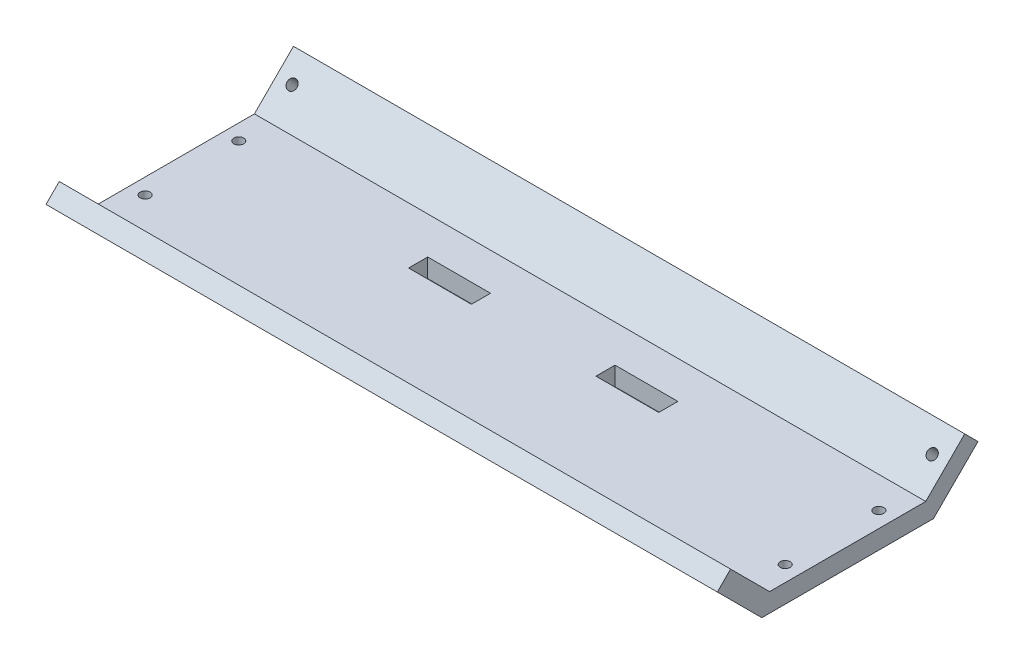
SolidWorks part; units mm, degrees
ref_plane "Front Plane" through (0, 0, 0) normal (0, 0, 1) x (1, 0, 0)
ref_plane "Top Plane" through (0, 0, 0) normal (0, 1, 0) x (1, 0, 0)
ref_plane "Right Plane" through (0, 0, 0) normal (1, 0, 0) x (0, 0, -1)
sketch "Sketch2" plane through (0, 0, 0) normal (1, 0, 0) x (0, 0, -1)
  line L0 (-25, 0) -> (25, 0)
  line L1 (25, 0) -> (37.5, 12.5)
  line L2 (-25, 0) -> (-37.5, 12.5)
  line L8 (27.4853, -6) -> (41.7426, 8.2574)
  line L9 (-27.4853, -6) -> (27.4853, -6)
  line L10 (-27.4853, -6) -> (-41.7426, 8.2574)
  line L11 (-37.5, 12.5) -> (-41.7426, 8.2574)
  line L12 (37.5, 12.5) -> (41.7426, 8.2574)
  line L13 (-37.5, 12.5) -> (-50, 25) construction
  line L14 (37.5, 12.5) -> (50, 25) construction
  point P4 (0, 0)
  dimension "D2" = 135
  dimension "D3" = 135
  dimension "D1" = 100
  dimension "D4" = 25
  dimension "D5" = 6
extrude "Main" add sketch "Sketch2" along normal mid plane 215
hole_wizard "Ø4.0mm Dowel Hole2" positions "3DSketch2" profile "Sketch4" hole size "Ø4.0" standard "ANSI Metric" end condition through all
sketch3d "3DSketch2"
  line L2 (107.5, 0, -25) -> (-107.5, 0, -25) construction
  line L3 (-102.5, 0, -25) -> (-102.5, 0, -15) construction
  line L4 (-102.5, 0, -15) -> (-102.5, 0, 15) construction
  line L5 (-102.5, 0, 15) -> (-102.5, 0, 25) construction
  line L6 (107.5, 0, 25) -> (-107.5, 0, 25) construction
  line L11 (102.5, 0, -25) -> (102.5, 0, -15) construction
  line L12 (102.5, 0, -15) -> (102.5, 0, 15) construction
  line L13 (102.5, 0, 15) -> (102.5, 0, 25) construction
  line L27 (102.5, 0, -25) -> (102.5, 7.0711, -32.0711) construction
  line L29 (102.5, 0, 25) -> (102.5, 7.0711, 32.0711) construction
  line L31 (-102.5, 7.0711, 32.0711) -> (-102.5, 0, 25) construction
  line L35 (-102.5, 7.0711, -32.0711) -> (-107.5, 7.0711, -32.0711) construction
  line L36 (-107.5, 12.5, -37.5) -> (-107.5, 0, -25) construction
  line L38 (-102.5, 7.0711, 32.0711) -> (-107.5, 7.0711, 32.0711) construction
  line L39 (-107.5, 0, 25) -> (-107.5, 12.5, 37.5) construction
  line L41 (102.5, 7.0711, -32.0711) -> (107.5, 7.0711, -32.0711) construction
  line L42 (107.5, 12.5, -37.5) -> (107.5, 0, -25) construction
  line L44 (102.5, 7.0711, 32.0711) -> (107.5, 7.0711, 32.0711) construction
  line L45 (107.5, 0, 25) -> (107.5, 12.5, 37.5) construction
  line L47 (102.5, 0, 25) -> (107.5, 0, 25) construction
  line L49 (-102.5, 0, 25) -> (-107.5, 0, 25) construction
  line L51 (-102.5, 7.0711, -32.0711) -> (-102.5, 0, -25) construction
  point P0 (-102.5, 7.0711, -32.0711)
  point P2 (-102.5, 0, -15)
  point P4 (-102.5, 0, 15)
  point P6 (-102.5, 7.0711, 32.0711)
  point P8 (102.5, 7.0711, 32.0711)
  point P10 (102.5, 0, 15)
  point P12 (102.5, 0, -15)
  point P14 (102.5, 7.0711, -32.0711)
  dimension "D1" = 5
  dimension "D2" = 10
  dimension "D3" = 10
sketch "Sketch4" plane through (-102.5, 7.0711, -32.0711) normal (1, 0, 0) x (0, -0.7071, 0.7071)
  line L0 (0, 0) -> (0, 16.0815)
  line L1 (0, 16.0815) -> (1.6, 16.0815)
  line L2 (1.6, 16.0815) -> (1.6, 0)
  line L5 (1.6, 0) -> (0, 0)
  line L11 (0, -6.35) -> (0, 107.95) construction
  dimension "Thru Hole Dia." = 3.2
  dimension "Thru Hole Depth" = 16.0815
sketch "Sketch5" plane through (0, 0, 0) normal (0, 1, 0) x (1, 0, 0)
  line L1 (-33.5, 21) -> (33.5, 21) construction
  line L2 (-33.5, 21) -> (-33.5, -21) construction
  line L3 (-33.5, -21) -> (33.5, -21) construction
  line L4 (33.5, 21) -> (33.5, -21) construction
  line L5 (-33.5, 21) -> (33.5, -21) construction
  line L6 (-33.5, -21) -> (33.5, 21) construction
  circle A0 centre (-33.5, 21) radius 3.5
  circle A1 centre (33.5, 21) radius 3.5
  circle A2 centre (-33.5, -21) radius 3.5
  circle A3 centre (33.5, -21) radius 3.5
  circle A4 centre (-33.5, 21) radius 1.55
  circle A5 centre (33.5, 21) radius 1.55
  circle A6 centre (33.5, -21) radius 1.55
  circle A7 centre (-33.5, -21) radius 1.55
  point P0 (0, 0)
  dimension "D1" = 7
  dimension "D2" = 3.1
  dimension "D3" = 42
  dimension "D4" = 67
extrude "Boss-Extrude1" [suppressed] add sketch "Sketch5" along normal blind 12
sketch "Sketch6" plane through (0, 0, 0) normal (0, 1, 0) x (1, 0, 0)
  line L0 (0, 0) -> (0, 10) construction
  line L1 (19.9375, 13.0625) -> (40.0625, 13.0625)
  line L2 (19.9375, 13.0625) -> (19.9375, 6.9375)
  line L3 (19.9375, 6.9375) -> (40.0625, 6.9375)
  line L4 (40.0625, 13.0625) -> (40.0625, 6.9375)
  line L5 (19.9375, 13.0625) -> (40.0625, 6.9375) construction
  line L6 (19.9375, 6.9375) -> (40.0625, 13.0625) construction
  line L7 (30, 10) -> (0, 10) construction
  line L8 (-40.0625, 13.0625) -> (-19.9375, 13.0625)
  line L9 (-40.0625, 13.0625) -> (-40.0625, 6.9375)
  line L10 (-40.0625, 6.9375) -> (-19.9375, 6.9375)
  line L11 (-19.9375, 13.0625) -> (-19.9375, 6.9375)
  line L12 (-40.0625, 13.0625) -> (-19.9375, 6.9375) construction
  line L13 (-40.0625, 6.9375) -> (-19.9375, 13.0625) construction
  line L14 (0, 10) -> (-30, 10) construction
  point P0 (30, 10)
  point P5 (-30, 10)
  dimension "D1" = 80.125
  dimension "D2" = 6.125
  dimension "D3" = 39.875
  dimension "D4" = 10
extrude "Shelf cut" cut sketch "Sketch6" against normal through all
equation "\"length\" = 215mm"
equation "\"D1@Main\" = \"length\""
equation "\"width\" = 220mm"
equation "\"height\" = 100mm"
equation "\"skin_th\" = 6mm"
equation "\"D5@Sketch2\"=\"skin_th\""
equation "\"D1@Sketch2\"=\"height\""
equation "\"shelf_height\" = 10mm"
equation "\"D4@Sketch6\"=\"shelf_height\""
